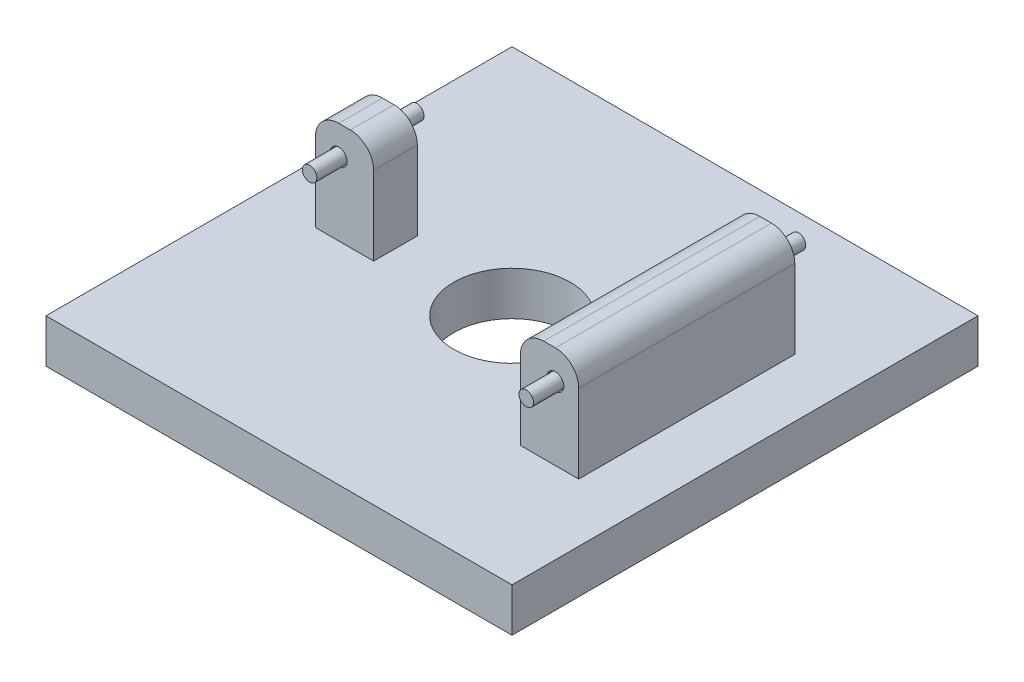
SolidWorks part; units mm, degrees
ref_plane "Front Plane" through (0, 0, 0) normal (0, 0, 1) x (1, 0, 0)
ref_plane "Top Plane" through (0, 0, 0) normal (0, 1, 0) x (1, 0, 0)
ref_plane "Right Plane" through (0, 0, 0) normal (1, 0, 0) x (0, 0, -1)
sketch "Sketch3" plane through (0, 0, 0) normal (0, 1, 0) x (1, 0, 0)
  line L1 (-25.4, 25.4) -> (25.4, 25.4)
  line L2 (-25.4, 25.4) -> (-25.4, -25.4)
  line L3 (-25.4, -25.4) -> (25.4, -25.4)
  line L4 (25.4, 25.4) -> (25.4, -25.4)
  line L5 (-25.4, 25.4) -> (25.4, -25.4) construction
  line L6 (-25.4, -25.4) -> (25.4, 25.4) construction
  point P0 (0, 0)
  dimension "D1" = 50.8
  dimension "D2" = 50.8
extrude "Boss-Extrude2" add sketch "Sketch3" along normal blind 4.7625
sketch "Sketch4" plane through (0, 4.7625, 0) normal (0, 1, 0) x (1, 0, 0)
  circle A0 centre (0, 0) radius 6.35
extrude "Cut-Extrude2" cut sketch "Sketch4" against normal through all
sketch "Sketch5" plane through (0, 4.7625, 0) normal (0, 1, 0) x (1, 0, 0)
  line L1 (-19.05, 2.3813) -> (-12.7, 2.3813)
  line L2 (-19.05, 2.3813) -> (-19.05, -2.3812)
  line L3 (-19.05, -2.3812) -> (-12.7, -2.3812)
  line L4 (-12.7, 2.3813) -> (-12.7, -2.3812)
  line L9 (0, 0) -> (0, 19.1256) construction
  line L10 (19.05, -11.7792) -> (12.7, -11.7792)
  line L11 (19.05, 11.7792) -> (12.7, 11.7792)
  line L12 (19.05, 11.7792) -> (19.05, -11.7792)
  line L13 (12.7, 11.7792) -> (12.7, -11.7792)
  line L14 (-25.4, 0) -> (63.5, 0) construction
  line L16 (-25.4, 25.4) -> (-25.4, -25.4) construction
  point P4 (-19.05, 0)
  point P5 (19.05, 0)
  dimension "D1" = 4.7625
  dimension "D2" = 6.35
  dimension "D3" = 12.7
  dimension "D4" = 23.5585
  dimension "D5" = 12.7
  dimension "D6" = 6.35
extrude "Boss-Extrude3" add sketch "Sketch5" along normal blind 11.1125
sketch "Sketch7" plane through (0, 0, 25.4) normal (0, 0, 1) x (1, 0, 0)
  line L0 (-19.05, 15.875) -> (-12.7, 15.875) construction
  line L1 (-19.05, 15.875) -> (-19.05, 4.7625) construction
  line L2 (12.7, 15.875) -> (19.05, 15.875) construction
  line L3 (12.7, 15.875) -> (12.7, 4.7625) construction
  circle A0 centre (-15.24, 12.7) radius 0.7937
  circle A1 centre (16.51, 12.7) radius 0.7937
  dimension "D1" = 1.5875
  dimension "D2" = 3.175
  dimension "D3" = 3.81
  dimension "D4" = 3.175
  dimension "D5" = 3.81
sketch "Sketch8" plane through (0, 0, 2.3812) normal (0, 0, 1) x (1, 0, 0)
  circle A2 centre (16.51, 12.7) radius 0.7937
  circle A4 centre (-16.51, 12.7) radius 0.9208
  point P0 (0, 0)
  dimension "D2" = 1.8415
extrude "Cut-Extrude5" cut sketch "Sketch8" against normal through all and the other way through all
sketch "Sketch9" plane through (0, 0, 2.3812) normal (0, 0, 1) x (1, 0, 0)
  circle A0 centre (-16.51, 12.7) radius 0.7937
  circle A1 centre (16.51, 12.7) radius 0.7937
  dimension "D1" = 1.5875
extrude "Boss-Extrude5" add sketch "Sketch9" along normal blind 3.175 and the other way blind 8.509
sketch "Sketch10" plane through (0, 0, 11.7792) normal (0, 0, 1) x (1, 0, 0)
  circle A1 centre (16.51, 12.7) radius 0.9208
  dimension "D1" = 1.8415
extrude "Cut-Extrude6" cut sketch "Sketch10" against normal up to next
sketch "Sketch11" plane through (0, 0, 11.7792) normal (0, 0, 1) x (1, 0, 0)
  circle A0 centre (16.51, 12.7) radius 0.7937 construction
  circle A1 centre (16.51, 12.7) radius 0.7937
extrude "Boss-Extrude6" add sketch "Sketch11" along normal blind 3.175 and the other way blind 26.5002 separate body
fillet "Fillet1" radius 2.54 4 edges at (19.05, 15.875, 0) (12.7, 15.875, 0) (-19.05, 15.875, 0) (-12.7, 15.875, 0)
